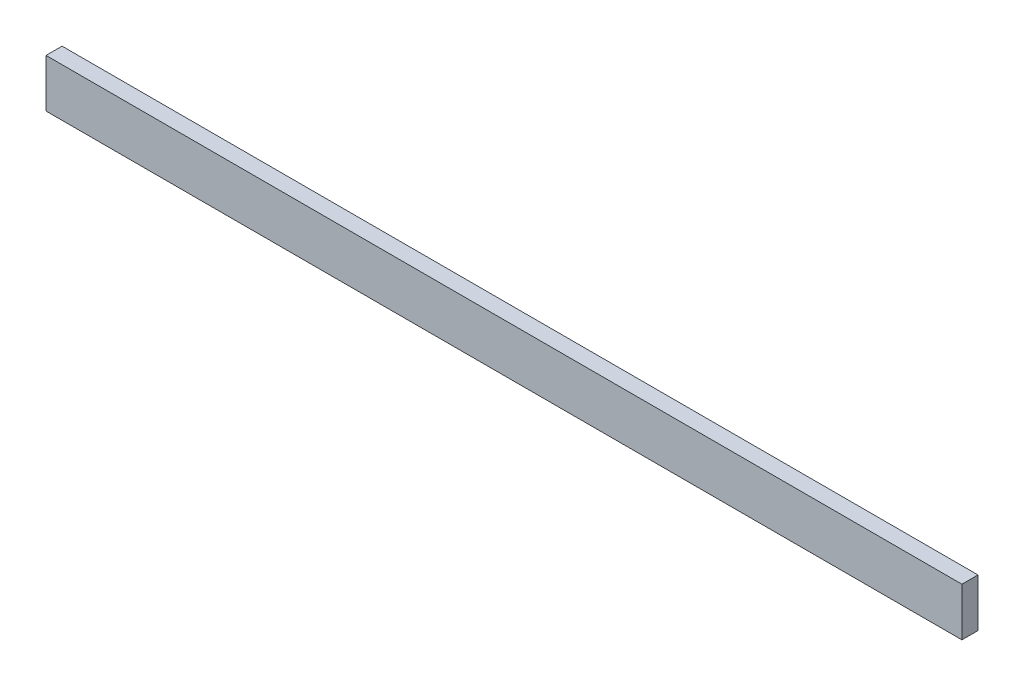
SolidWorks part; units mm, degrees
ref_plane "Front Plane" through (0, 0, 0) normal (0, 0, 1) x (1, 0, 0)
ref_plane "Top Plane" through (0, 0, 0) normal (0, 1, 0) x (1, 0, 0)
ref_plane "Right Plane" through (0, 0, 0) normal (1, 0, 0) x (0, 0, -1)
sketch "Sketch2" plane through (0, 0, 0) normal (0, 0, 1) x (1, 0, 0)
  line L1 (0, 0) -> (723.9, 0)
  line L2 (0, 0) -> (0, 38.1)
  line L3 (0, 38.1) -> (723.9, 38.1)
  line L4 (723.9, 0) -> (723.9, 38.1)
  dimension "D1" = 723.9
  dimension "D2" = 38.1
extrude "Boss-Extrude1" add sketch "Sketch2" along normal blind 12.7
